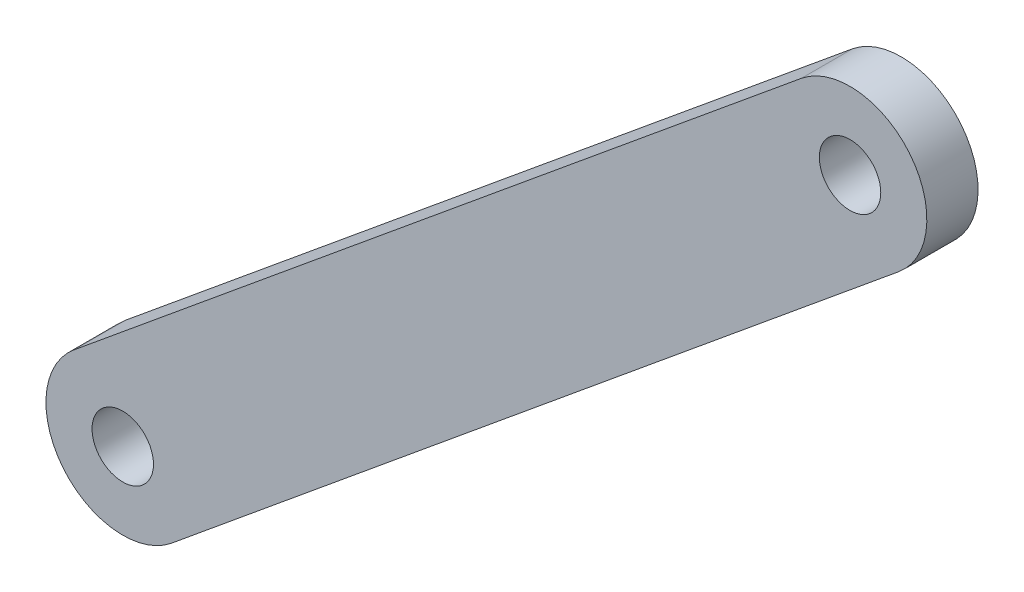
SolidWorks part; units mm, degrees
ref_plane "Plan de face" through (0, 0, 0) normal (0, 0, 1) x (1, 0, 0)
ref_plane "Plan de dessus" through (0, 0, 0) normal (0, 1, 0) x (1, 0, 0)
ref_plane "Plan de droite" through (0, 0, 0) normal (1, 0, 0) x (0, 0, -1)
sketch "Esquisse1" plane through (0, 0, 0) normal (0, 0, 1) x (1, 0, 0)
  line L0 (20, 0) -> (-51.0249, -58.4761) construction
  line L1 (24.7671, -5.7901) -> (-46.2579, -64.2662)
  line L2 (15.2329, 5.7901) -> (-55.792, -52.686)
  arc A0 (24.7671, -5.7901) -> (15.2329, 5.7901) centre (20, 0) ccw
  arc A1 (-55.792, -52.686) -> (-46.2579, -64.2662) centre (-51.0249, -58.4761) ccw
  point P4 (-15.5125, -29.2381)
  dimension "D1" = 15
extrude "Boss.-Extru.1" add sketch "Esquisse1" along normal blind 5 from offset 10 offset against normal yes
sketch "Esquisse2" plane through (0, 0, -5) normal (0, 0, 1) x (1, 0, 0)
  circle A0 centre (20, 0) radius 3
  circle A1 centre (-51.0249, -58.4761) radius 3
  dimension "D1" = 6
  dimension "D2" = 6
extrude "Enlèv. mat.-Extru.1" cut sketch "Esquisse2" against normal up to vertex (5 mm away) contours A1 | A0
